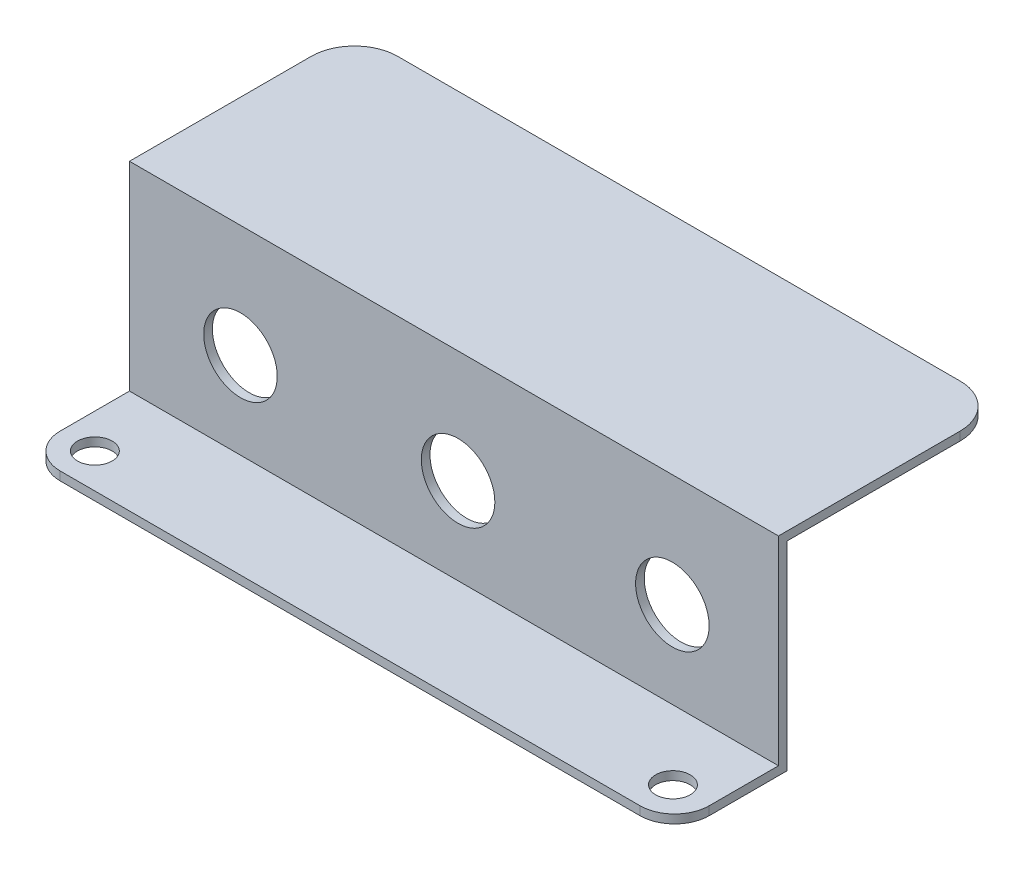
SolidWorks part; units mm, degrees
ref_plane "Front Plane" through (0, 0, 0) normal (0, 0, 1) x (1, 0, 0)
ref_plane "Top Plane" through (0, 0, 0) normal (0, 1, 0) x (1, 0, 0)
ref_plane "Right Plane" through (0, 0, 0) normal (1, 0, 0) x (0, 0, -1)
sketch "Sketch1" plane through (0, 0, 0) normal (0, 1, 0) x (1, 0, 0)
  line L1 (-50, -15) -> (25, -15)
  line L2 (-50, -15) -> (-50, 10)
  line L3 (-50, 10) -> (25, 10)
  line L4 (25, -15) -> (25, 10)
  point P0 (0, 0)
  dimension "D1" = 75
  dimension "D2" = 25
extrude "Boss-Extrude1" add sketch "Sketch1" along normal blind 1
sketch "Sketch3" plane through (0, 0, 15) normal (0, 0, 1) x (1, 0, 0)
  line L0 (25, 1) -> (25, 0) construction
  line L1 (-50, 1) -> (25, 1)
  line L2 (-50, 1) -> (-50, -23)
  line L3 (-50, -23) -> (25, -23)
  line L4 (25, 1) -> (25, -23)
  line L5 (-50, 1) -> (25, 1) construction
  dimension "D1" = 24
extrude "Boss-Extrude2" add sketch "Sketch3" along normal blind 1
sketch "Sketch4" plane through (0, -23, 0) normal (0, -1, 0) x (1, 0, 0)
  line L0 (25, 15) -> (25, -10) construction
  line L1 (-50, 16) -> (25, 16)
  line L2 (-50, 16) -> (-50, 28)
  line L3 (-50, 28) -> (25, 28)
  line L4 (25, 16) -> (25, 28)
  line L5 (25, 24) -> (20.8059, 24) construction
  circle A1 centre (20.8059, 24) radius 2
  circle A3 centre (-46, 24) radius 2
  point P7 (0, 0)
  point P9 (0, 0)
  dimension "D1" = 4
  dimension "D2" = 4
  dimension "D3" = 4
  dimension "D4" = 12
  dimension "D5" = 4.1941
extrude "Boss-Extrude3" add sketch "Sketch4" against normal blind 1
fillet "Fillet1" radius 4 2 edges at (-50, -22.5, 28) (25, -22.5, 28)
sketch "Sketch6" plane through (0, 0, 16) normal (0, 0, 1) x (1, 0, 0)
  line L0 (-37.173, -22) -> (-37.173, -12) construction
  line L1 (-12.0269, -22) -> (-12.0269, -12) construction
  line L3 (12.7381, -22) -> (12.7381, -12) construction
  circle A0 centre (-37.173, -12) radius 4.25
  circle A1 centre (-12.0269, -12) radius 4.25
  circle A2 centre (12.7381, -12) radius 4.25
  dimension "D1" = 8.5
  dimension "D2" = 10
extrude "Cut-Extrude2" cut sketch "Sketch6" against normal up to next
fillet "Fillet2" radius 5 2 edges at (25, 0.5, -10) (-50, 0.5, -10)
